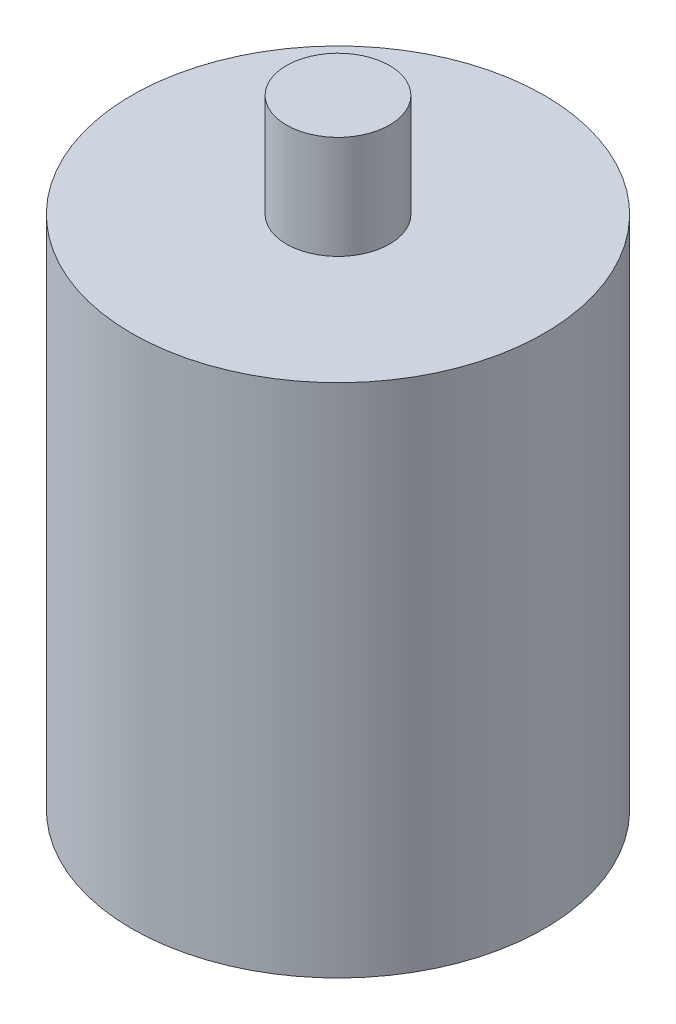
SolidWorks part; units mm, degrees
ref_plane "Front Plane" through (0, 0, 0) normal (0, 0, 1) x (1, 0, 0)
ref_plane "Top Plane" through (0, 0, 0) normal (0, 1, 0) x (1, 0, 0)
ref_plane "Right Plane" through (0, 0, 0) normal (1, 0, 0) x (0, 0, -1)
sketch "Sketch1" plane through (0, 0, 0) normal (0, 1, 0) x (1, 0, 0)
  circle A0 centre (0, 0) radius 20
  dimension "D1" = 40
extrude "Boss-Extrude1" add sketch "Sketch1" along normal blind 50
sketch "Sketch2" plane through (0, 50, 0) normal (0, 1, 0) x (1, 0, 0)
  circle A0 centre (0, 0) radius 5
  dimension "D1" = 10
extrude "Boss-Extrude2" add sketch "Sketch2" along normal blind 10
sketch "Sketch3" plane through (0, 0, 0) normal (0, 0, 1) x (1, 0, 0)
  line L0 (0, 0) -> (0, 68.5672) construction
  circle A0 centre (0, 55.8365) radius 1.5
  dimension "D1" = 3
extrude "Cut-Extrude1" cut sketch "Sketch3" against normal blind 16
